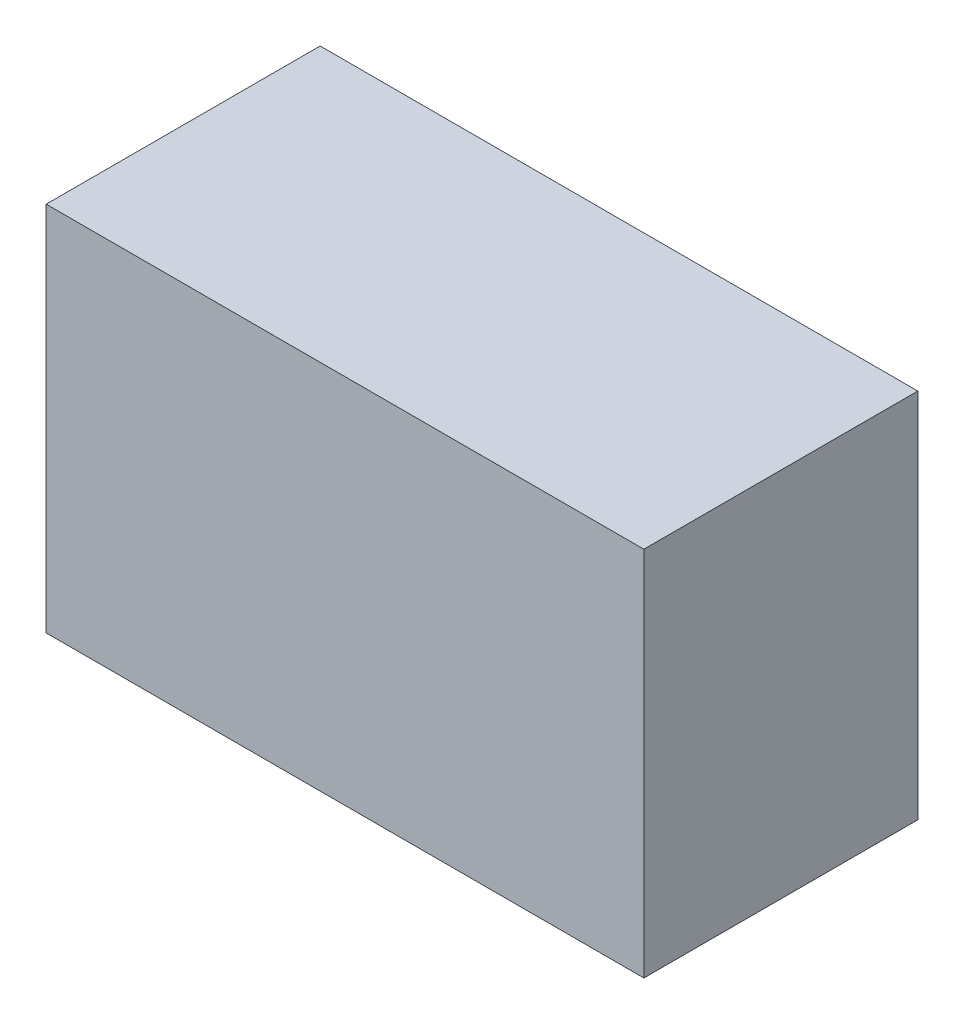
SolidWorks part; units mm, degrees
material "6061-T6 (SS)"
ref_plane "X-Y Datum" through (0, 0, 0) normal (0, 0, 1) x (1, 0, 0)
ref_plane "X-Z Datum" through (0, 0, 0) normal (0, 1, 0) x (1, 0, 0)
ref_plane "Y-Z Datum" through (0, 0, 0) normal (1, 0, 0) x (0, 0, -1)
sketch "Sketch1" plane through (0, 0, 0) normal (0, 1, 0) x (1, 0, 0)
  line L1 (0, 0) -> (86.868, 0)
  line L2 (0, 0) -> (0, 39.8145)
  line L3 (0, 39.8145) -> (86.868, 39.8145)
  line L4 (86.868, 0) -> (86.868, 39.8145)
  dimension "D1" = 86.868
  dimension "D2" = 39.8145
extrude "Boss-Extrude1" add sketch "Sketch1" along normal blind 53.975
